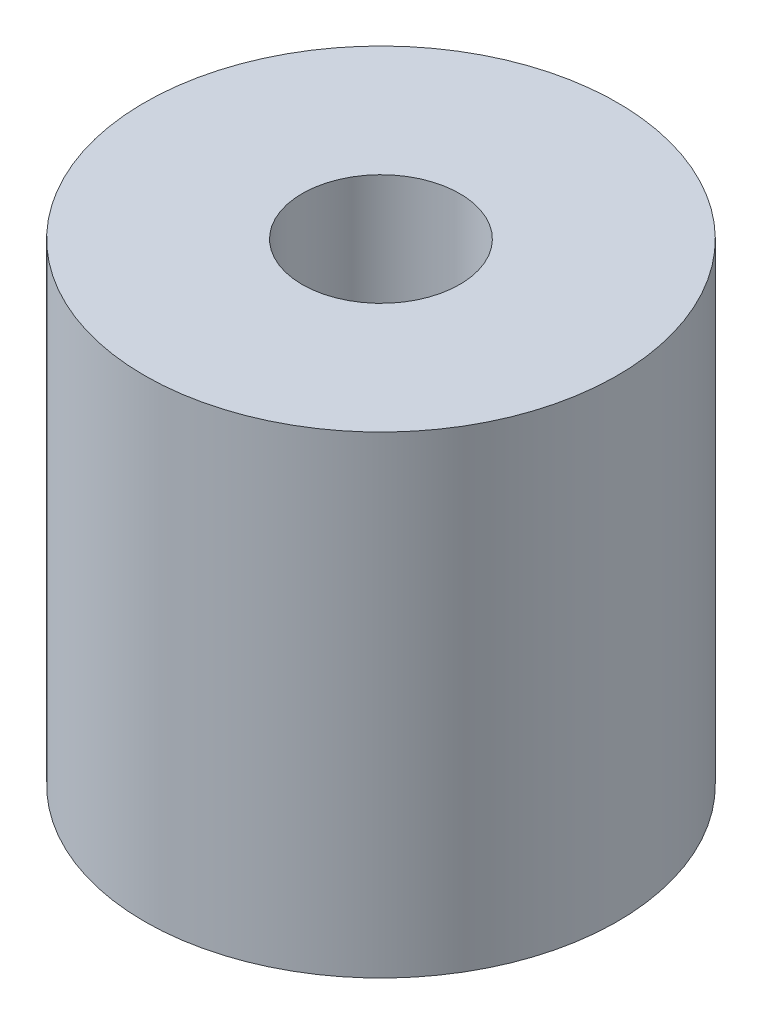
SolidWorks part; units mm, degrees
ref_plane "Front Plane" through (0, 0, 0) normal (0, 0, 1) x (1, 0, 0)
ref_plane "Top Plane" through (0, 0, 0) normal (0, 1, 0) x (1, 0, 0)
ref_plane "Right Plane" through (0, 0, 0) normal (1, 0, 0) x (0, 0, -1)
sketch "Sketch1" plane through (0, 0, 0) normal (0, 1, 0) x (1, 0, 0)
  circle A0 centre (0, 0) radius 6
  circle A1 centre (0, 0) radius 2
  dimension "D1" = 12
  dimension "D2" = 4
extrude "Boss-Extrude1" add sketch "Sketch1" along normal blind 12
